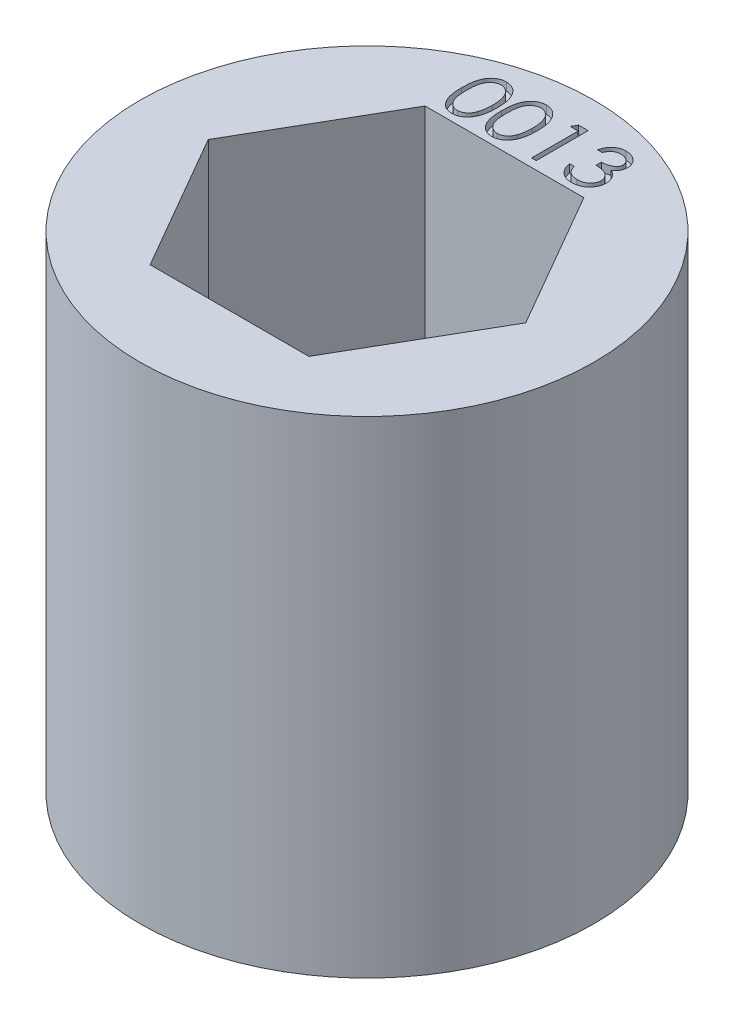
SolidWorks part; units mm, degrees
material "Nylon 101"
ref_plane "Front Plane" through (0, 0, 0) normal (0, 0, 1) x (1, 0, 0)
ref_plane "Top Plane" through (0, 0, 0) normal (0, 1, 0) x (1, 0, 0)
ref_plane "Right Plane" through (0, 0, 0) normal (1, 0, 0) x (0, 0, -1)
sketch "Sketch1" plane through (0, 0, 0) normal (0, 1, 0) x (1, 0, 0)
  line L1 (7.7723, 0) -> (3.8861, 6.731)
  line L2 (3.8861, 6.731) -> (-3.8861, 6.731)
  line L3 (-3.8861, 6.731) -> (-7.7723, 0)
  line L4 (-7.7723, 0) -> (-3.8861, -6.731)
  line L5 (-3.8861, -6.731) -> (3.8861, -6.731)
  line L6 (3.8861, -6.731) -> (7.7723, 0)
  circle A0 centre (0, 0) radius 11.1125
  circle A1 centre (0, 0) radius 6.731 construction
  dimension "D2" = 22.225
  dimension "D1" = 13.462
extrude "Boss-Extrude1" add sketch "Sketch1" along normal blind 23.8125
sketch "Sketch2" plane through (0, 23.8125, 0) normal (0, 1, 0) x (1, 0, 0)
  line L0 (-3.8652, 7.1374) -> (3.2102, 7.1374) construction
  line L1 (3.8861, 6.731) -> (-3.8861, 6.731) construction
  text T0 "0013" font "Century Gothic" height 2.54
  dimension "D1" = 0.4064
extrude "Cut-Extrude1" cut sketch "Sketch2" against normal blind 0.4
